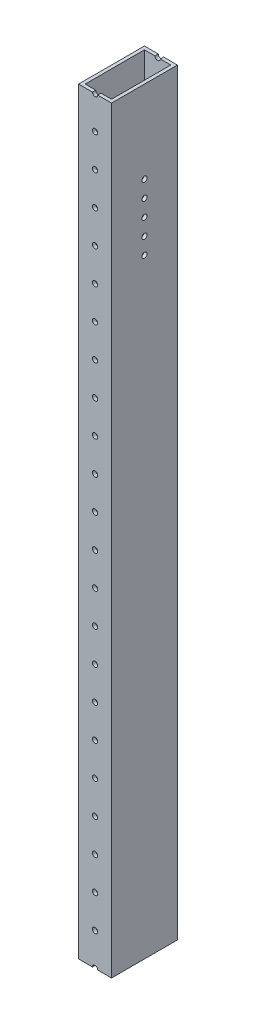
SolidWorks part; units mm, degrees
ref_plane "Front Plane" through (0, 0, 0) normal (0, 0, 1) x (1, 0, 0)
ref_plane "Top Plane" through (0, 0, 0) normal (0, 1, 0) x (1, 0, 0)
ref_plane "Right Plane" through (0, 0, 0) normal (1, 0, 0) x (0, 0, -1)
sketch "Sketch1" plane through (0, 0, 0) normal (0, 1, 0) x (1, 0, 0)
  line L0 (-10.16, 22.86) -> (10.16, 22.86)
  line L1 (-12.7, -25.4) -> (12.7, -25.4)
  line L2 (-12.7, -25.4) -> (-12.7, 25.4)
  line L3 (-12.7, 25.4) -> (12.7, 25.4)
  line L4 (12.7, -25.4) -> (12.7, 25.4)
  line L5 (-12.7, -25.4) -> (12.7, 25.4) construction
  line L6 (-12.7, 25.4) -> (12.7, -25.4) construction
  line L7 (10.16, -22.86) -> (10.16, 22.86)
  line L8 (-10.16, -22.86) -> (10.16, -22.86)
  line L9 (-10.16, -22.86) -> (-10.16, 22.86)
  point P0 (0, 0)
  dimension "D1" = 50.8
  dimension "D2" = 25.4
  dimension "D3" = 2.54
extrude "Boss-Extrude1" add sketch "Sketch1" along normal blind 584.2
sketch "Sketch2" plane through (0, 0, 25.4) normal (0, 0, 1) x (1, 0, 0)
  line L0 (-12.7, 0) -> (12.7, 0) construction
  circle A0 centre (0, 0) radius 2.032
  circle A1 centre (0, 25.4) radius 2.032
  circle A2 centre (0, 50.8) radius 2.032
  circle A3 centre (0, 76.2) radius 2.032
  circle A4 centre (0, 101.6) radius 2.032
  circle A5 centre (0, 127) radius 2.032
  circle A6 centre (0, 152.4) radius 2.032
  circle A7 centre (0, 177.8) radius 2.032
  circle A8 centre (0, 203.2) radius 2.032
  circle A9 centre (0, 228.6) radius 2.032
  circle A10 centre (0, 254) radius 2.032
  circle A11 centre (0, 279.4) radius 2.032
  circle A12 centre (0, 304.8) radius 2.032
  circle A13 centre (0, 330.2) radius 2.032
  circle A14 centre (0, 355.6) radius 2.032
  circle A15 centre (0, 381) radius 2.032
  circle A16 centre (0, 406.4) radius 2.032
  circle A17 centre (0, 431.8) radius 2.032
  circle A18 centre (0, 457.2) radius 2.032
  circle A19 centre (0, 482.6) radius 2.032
  circle A20 centre (0, 508) radius 2.032
  circle A21 centre (0, 533.4) radius 2.032
  circle A22 centre (0, 558.8) radius 2.032
  circle A23 centre (0, 584.2) radius 2.032
  dimension "D1" = 4.064
  dimension "D2" = 24
extrude "Cut-Extrude1" cut sketch "Sketch2" against normal through all
sketch "Sketch3" plane through (-12.7, 0, 0) normal (-1, 0, 0) x (0, 0, 1)
  line L0 (0, 584.2) -> (0, 520.7) construction
  line L1 (-25.4, 584.2) -> (25.4, 584.2) construction
  circle A0 centre (0, 520.7) radius 2.032
  circle A1 centre (0, 508) radius 2.032
  circle A2 centre (0, 495.3) radius 2.032
  circle A3 centre (0, 482.6) radius 2.032
  circle A4 centre (0, 469.9) radius 2.032
  dimension "D1" = 4.064
  dimension "D2" = 63.5
  dimension "D3" = 5
extrude "Cut-Extrude2" cut sketch "Sketch3" against normal through all
